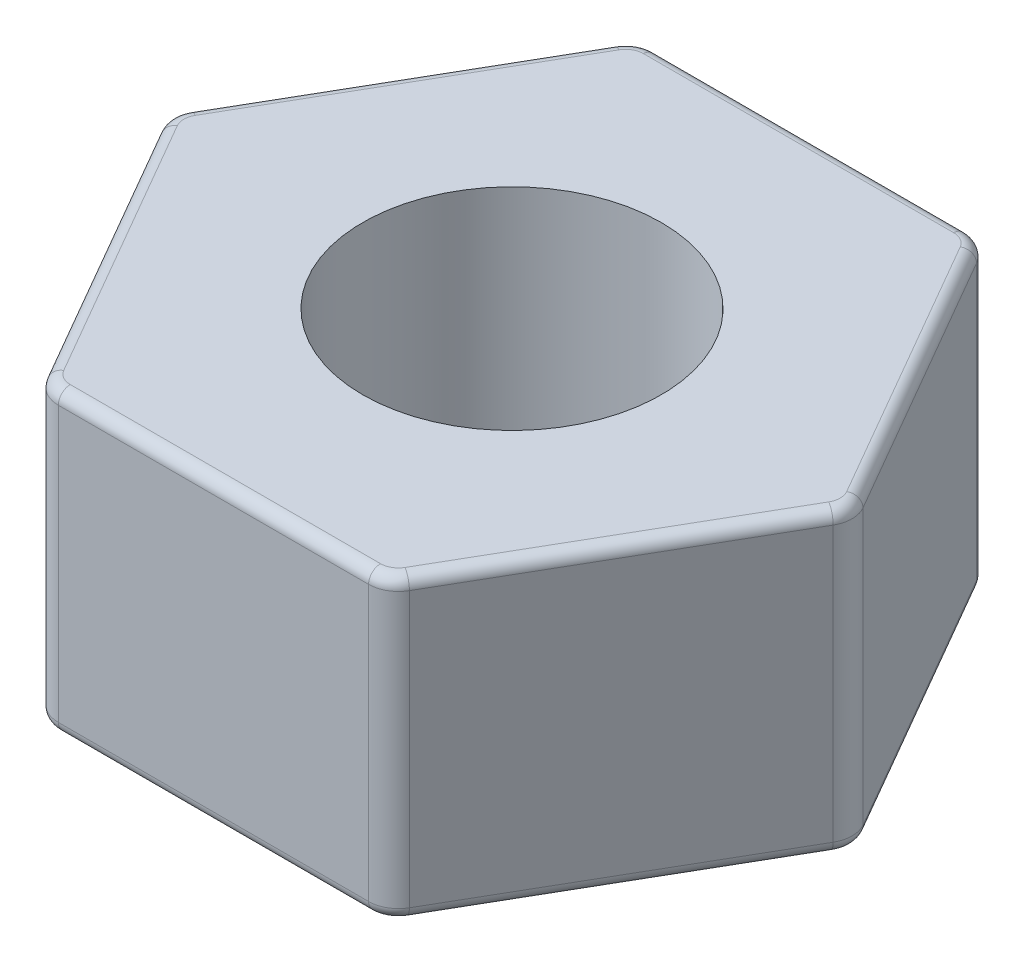
SolidWorks part; units mm, degrees
material "acero"
ref_plane "Alzado" through (0, 0, 0) normal (0, 0, 1) x (1, 0, 0)
ref_plane "Planta" through (0, 0, 0) normal (0, 1, 0) x (1, 0, 0)
ref_plane "Vista lateral" through (0, 0, 0) normal (1, 0, 0) x (0, 0, -1)
sketch "Croquis1" plane through (0, 0, 0) normal (0, 1, 0) x (1, 0, 0)
  line L1 (-2.8868, 5) -> (-5.7735, 0)
  line L2 (-5.7735, 0) -> (-2.8868, -5)
  line L3 (-2.8868, -5) -> (2.8868, -5)
  line L4 (2.8868, -5) -> (5.7735, 0)
  line L5 (5.7735, 0) -> (2.8868, 5)
  line L6 (2.8868, 5) -> (-2.8868, 5)
  circle A0 centre (0, 0) radius 5 construction
  circle A1 centre (0, 0) radius 2.5
  dimension "D1" = 5
  dimension "D2" = 10
extrude "Saliente-Extruir1" add sketch "Croquis1" along normal blind 5
fillet "Redondeo1" radius 0.5 6 edges at (-2.8868, 2.5, -5) (2.8868, 2.5, -5) (5.7735, 2.5, 0) (2.8868, 2.5, 5) (-5.7735, 2.5, 0) (-2.8868, 2.5, 5)
sketch "Croquis2" plane through (0, 5, 0) normal (0, 1, 0) x (1, 0, 0)
  circle A0 centre (0, 0) radius 5.6
  dimension "D1" = 11.2
fillet "Redondeo2" radius 0.2 24 edges at (-2.8481, 0, -4.933) (0, 0, -5) (2.8481, 0, -4.933) (4.3301, 0, -2.5) (5.6962, 0, 0) (4.3301, 0, 2.5) (2.8481, 0, 4.933) (0, 0, 5) (-2.8481, 0, 4.933) (-4.3301, 0, 2.5) (-5.6962, 0, 0) (-2.8481, 5, -4.933) (0, 5, -5) (2.8481, 5, -4.933) (4.3301, 5, -2.5) (5.6962, 5, 0) (4.3301, 5, 2.5) (2.8481, 5, 4.933) (0, 5, 5) (-2.8481, 5, 4.933) (-4.3301, 5, 2.5) (-5.6962, 5, 0) (-4.3301, 0, -2.5) (-4.3301, 5, -2.5)
